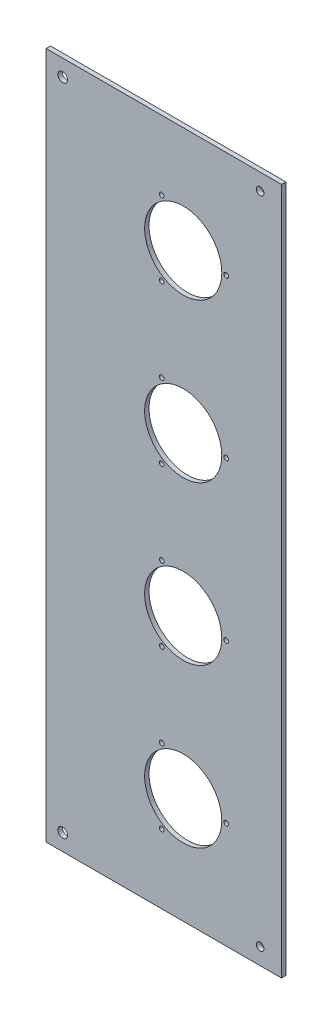
SolidWorks part; units mm, degrees
ref_plane "Front Plane" through (0, 0, 0) normal (1, 0, 0) x (0, 1, 0)
ref_plane "Top Plane" through (0, 0, 0) normal (0, 0, 1) x (0, 1, 0)
ref_plane "Right Plane" through (0, 0, 0) normal (0, 1, 0) x (-1, 0, 0)
sketch "Sketch1" plane through (0, 0, 0) normal (0, 0, 1) x (0, 1, 0)
  line L0 (0, 0) -> (0, 85.915) construction
  line L1 (-250, -85.915) -> (250, -85.915)
  line L2 (-250, -85.915) -> (-250, 85.915)
  line L3 (-250, 85.915) -> (250, 85.915)
  line L4 (250, -85.915) -> (250, 85.915)
  line L5 (-250, -85.915) -> (250, 85.915) construction
  line L6 (-250, 85.915) -> (250, -85.915) construction
  line L7 (-172.25, -14.085) -> (-57.42, -14.085) construction
  line L8 (-172.25, -45.305) -> (-172.25, -14.085) construction
  line L9 (-114.835, -14.085) -> (-114.835, 85.915) construction
  circle A0 centre (-237.5, 73.415) radius 3.5
  circle A1 centre (237.5, 73.415) radius 3.5
  circle A2 centre (-237.5, -69.915) radius 2.8
  circle A3 centre (237.5, -69.915) radius 2.8
  circle A4 centre (-172.25, -14.085) radius 28
  circle A5 centre (-57.42, -14.085) radius 28
  circle A6 centre (172.25, -14.085) radius 28
  circle A7 centre (57.42, -14.085) radius 28
  circle A8 centre (-172.25, -45.305) radius 1.7
  circle A9 centre (-199.2873, 1.525) radius 1.7
  circle A10 centre (-145.2127, 1.525) radius 1.7
  circle A11 centre (-30.3827, 1.525) radius 1.7
  circle A12 centre (-84.4573, 1.525) radius 1.7
  circle A13 centre (-57.42, -45.305) radius 1.7
  circle A14 centre (199.2873, 1.525) radius 1.7
  circle A15 centre (145.2127, 1.525) radius 1.7
  circle A16 centre (172.25, -45.305) radius 1.7
  circle A17 centre (84.4573, 1.525) radius 1.7
  circle A18 centre (30.3827, 1.525) radius 1.7
  circle A19 centre (57.42, -45.305) radius 1.7
  point P0 (0, 0)
  dimension "D5" = 7
  dimension "D8" = 5.6
  dimension "D15" = 56
  dimension "D18" = 3.4
  dimension "D1" = 171.83
  dimension "D2" = 500
  dimension "D3" = 12.5
  dimension "D4" = 12.5
  dimension "D6" = 12.5
  dimension "D7" = 12.5
  dimension "D9" = 12.5
  dimension "D10" = 16
  dimension "D11" = 12.5
  dimension "D12" = 16
  dimension "D13" = 77.75
  dimension "D14" = 100
  dimension "D16" = 114.83
  dimension "D17" = 31.22
  dimension "D19" = 3
extrude "Boss-Extrude1" add sketch "Sketch1" along normal blind 3.175 contours L1 L4 L3 L2 A19 A18 A17 A15 A13 A11 A10 A9 A8 A6 A5 A4 A3 A2 A1 A0 A7 A12 A14 A16
sketch "Sketch2" plane through (0, 0, 3.175) normal (0, 0, 1) x (1, 0, 0)
  line L1 (-85.915, 250) -> (85.915, 250)
  line L2 (-85.915, 250) -> (-85.915, -250)
  line L3 (-85.915, -250) -> (85.915, -250)
  line L4 (85.915, 250) -> (85.915, -250)
  line L5 (-85.915, 250) -> (85.915, -250) construction
  line L6 (-85.915, -250) -> (85.915, 250) construction
  line L7 (85.415, 249.5) -> (-85.415, 249.5)
  line L8 (85.415, 249.5) -> (85.415, -249.5)
  line L9 (85.415, -249.5) -> (-85.415, -249.5)
  line L10 (-85.415, 249.5) -> (-85.415, -249.5)
  line L11 (85.415, 249.5) -> (-85.415, -249.5) construction
  line L12 (85.415, -249.5) -> (-85.415, 249.5) construction
  point P0 (0, 0)
  point P7 (0, 0)
  dimension "D1" = 0.5
  dimension "D2" = 0.5
extrude "Cut-Extrude1" cut sketch "Sketch2" against normal blind 3.175
